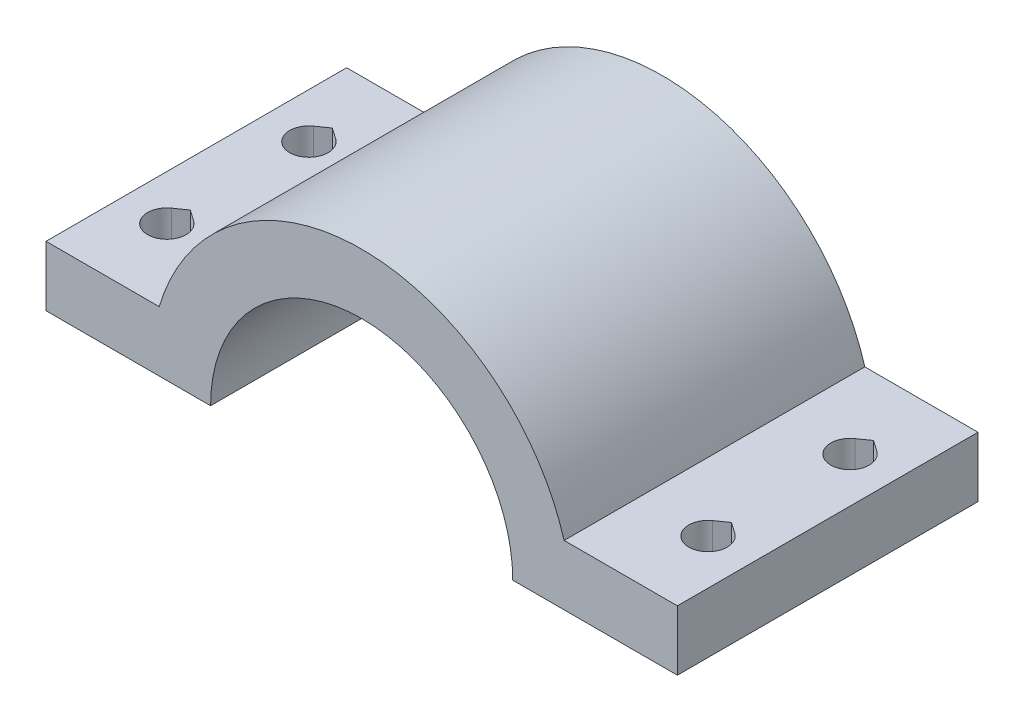
SolidWorks part; units mm, degrees
material "Custom Plastic"
ref_plane "X-Y Datum" through (0, 0, 0) normal (0, 0, 1) x (1, 0, 0)
ref_plane "X-Z Datum" through (0, 0, 0) normal (0, 1, 0) x (1, 0, 0)
ref_plane "Y-Z Datum" through (0, 0, 0) normal (1, 0, 0) x (0, 0, -1)
sketch "Sketch2" plane through (0, 0, 0) normal (0, 0, 1) x (1, 0, 0)
  line L1 (0, -17.8435) -> (0, 17.8435) construction
  line L10 (17.8435, 0) -> (-17.8435, 0) construction
  line L11 (-12.7635, 0) -> (-17.8435, 0)
  line L12 (-17.8435, 0) -> (-26.67, 0)
  line L13 (-26.67, 0) -> (-26.67, 5.08)
  line L14 (-26.67, 5.08) -> (-17.8435, 5.08)
  line L15 (-17.8435, 5.08) -> (-17.1051, 5.08)
  line L16 (-17.1051, 5.08) -> (-11.709, 5.08)
  line L17 (-17.8435, 5.08) -> (-17.8435, 0) construction
  line L18 (17.8435, 5.08) -> (17.1051, 5.08)
  line L19 (17.1051, 5.08) -> (11.709, 5.08)
  line L20 (12.7635, 0) -> (17.8435, 0)
  line L21 (17.8435, 0) -> (26.67, 0)
  line L22 (26.67, 0) -> (26.67, 5.08)
  line L23 (26.67, 5.08) -> (17.8435, 5.08)
  circle A0 centre (0, 0) radius 12.7635
  circle A1 centre (0, 0) radius 17.8435
  point P0 (0, 0)
  point P8 (0, 0)
  point P11 (0, 0)
  point P14 (0, 0)
  dimension "D1" = 25.527
  dimension "D4" = 5.08
  dimension "D2" = 13.9065
  dimension "D3" = 5.08
extrude "Boss-Extrude1" add sketch "Sketch2" along normal blind 25.4 contours A1 L15 L14 L13 L12 | L16 A1 L11 A0 | L19 A1 L16 A0 | L20 A1 L19 A0 | A1 L21 L22 L23 L18
sketch "Sketch3" plane through (0, 5.08, 0) normal (0, 1, 0) x (1, 0, 0)
  line L0 (-17.1051, 0) -> (-17.1051, -25.4) construction
  line L1 (-26.67, -7) -> (-17.1051, -7) construction
  line L2 (-26.67, -25.4) -> (-26.67, 0) construction
  line L3 (-26.67, -19) -> (-17.1051, -19) construction
  line L4 (-26.67, 0) -> (-17.1051, 0) construction
  line L5 (0, 0) -> (0, -25.4) construction
  line L6 (-17.1051, -25.4) -> (17.1051, -25.4) construction
  line L7 (-23.7921, -5.6689) -> (-22.86, -5.0162)
  line L8 (-22.86, -5.0162) -> (-22.86, -7) construction
  line L9 (-22.86, -5.0162) -> (-21.9279, -5.6689)
  line L10 (-22.86, -19) -> (-22.86, -17.0162) construction
  line L11 (-22.86, -17.0162) -> (-23.7921, -17.6689)
  line L12 (-22.86, -17.0162) -> (-21.9279, -17.6689)
  line L13 (22.86, -17.0162) -> (21.9279, -17.6689)
  line L14 (22.86, -17.0162) -> (23.7921, -17.6689)
  line L15 (22.86, -19) -> (22.86, -17.0162) construction
  line L16 (26.67, -19) -> (17.1051, -19) construction
  line L17 (26.67, -7) -> (17.1051, -7) construction
  line L18 (22.86, -5.0162) -> (22.86, -7) construction
  line L19 (22.86, -5.0162) -> (21.9279, -5.6689)
  line L20 (23.7921, -5.6689) -> (22.86, -5.0162)
  circle A4 centre (-22.86, -7) radius 1.625
  circle A5 centre (-22.86, -19) radius 1.625
  circle A6 centre (22.86, -19) radius 1.625
  circle A7 centre (22.86, -7) radius 1.625
  point P12 (-22.86, -7)
  point P13 (-22.86, -19)
  dimension "D3" = 3.25
  dimension "D4" = 3.25
  dimension "D1" = 7
  dimension "D2" = 12
  dimension "D5" = 55
  dimension "D6" = 3.81
  dimension "D7" = 55
extrude "Cut-Extrude1 Holes" cut sketch "Sketch3" against normal through all contours A4 | A4 L9 L7 | A5 | A5 L12 L11 | A6 | L13 A6 L14 | A7 | L19 A7 L20
equation "\"Clamp wall thickness\"= 0.2"
equation "\"clamp wall length\"=0.5475"
equation "\"Clamp ID\"= 1.005"
equation "\"D1@Sketch2\"=\"Clamp ID\""
equation "\"D4@Sketch2\"=\"Clamp wall thickness\""
equation "\"Clamp width\"= 1in"
equation "\"D2@Sketch2\"=\"clamp wall length\""
equation "\"D3@Sketch2\"=\"Clamp wall thickness\""
equation "\"D1@Boss-Extrude1\"=\"Clamp width\""
equation "\"Clamp hole diameter\"= 3.25mm'(3.25mmm)"
equation "\"Clamp hole distance b/w\"= 12mm'(12.0mm)"
equation "\"Clamp hole distance from wall\"= 7mm'(7mm)"
equation "\"D1@Sketch3\"=\"Clamp hole distance from wall\""
equation "\"D2@Sketch3\"=\"Clamp hole distance b/w\""
equation "\"D3@Sketch3\"=\"Clamp hole diameter\""
equation "\"D4@Sketch3\"=\"Clamp hole diameter\""
